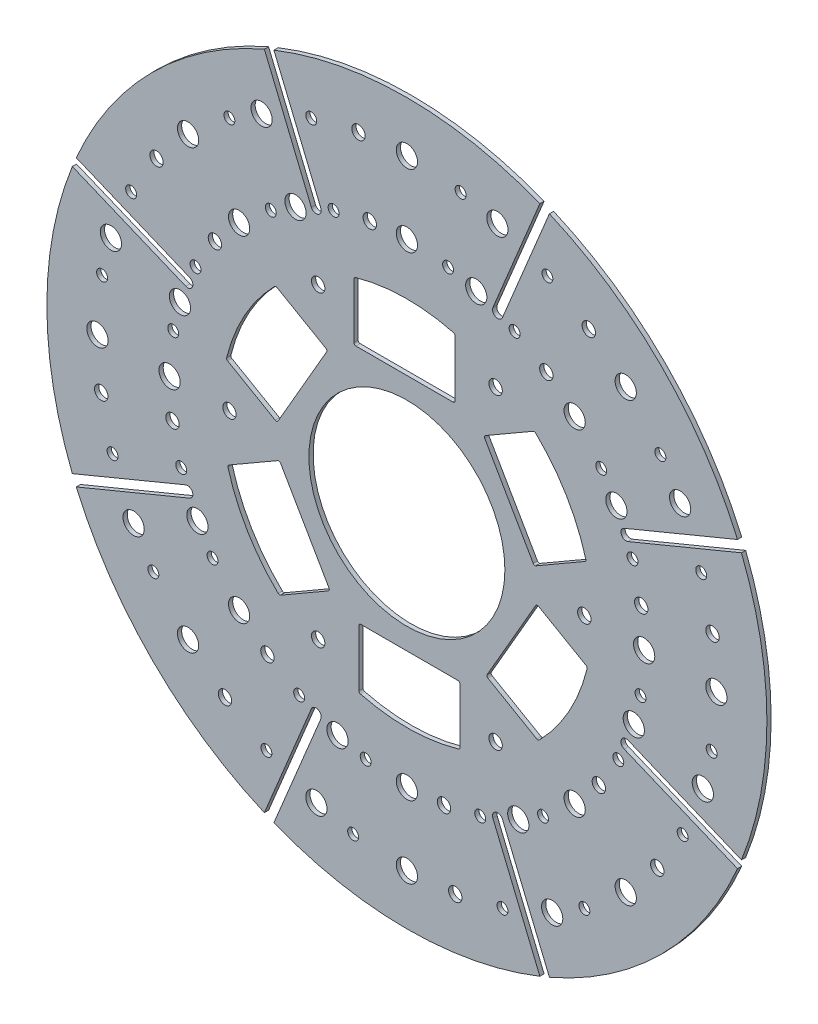
SolidWorks part; units mm, degrees
ref_plane "Plano frontal" through (0, 0, 0) normal (0, 0, 1) x (1, 0, 0)
ref_plane "Plano superior" through (0, 0, 0) normal (0, 1, 0) x (1, 0, 0)
ref_plane "Plano direito" through (0, 0, 0) normal (1, 0, 0) x (0, 0, -1)
sketch "Esboço1" plane through (0, 0, 0) normal (0, 0, 1) x (1, 0, 0)
  circle A0 centre (0, 0) radius 174.5
  circle A1 centre (0, 0) radius 47.5
  dimension "D1" = 95
  dimension "D2" = 349
extrude "Ressalto-extrusão1" add sketch "Esboço1" along normal blind 2.05
sketch "Esboço4" plane through (0, 0, 2.05) normal (0, 0, 1) x (1, 0, 0)
  line L0 (41.6989, 107.2029) -> (65.6818, 165.1028)
  line L1 (0, 115) -> (0, 0) construction
  line L5 (65.6818, 165.1028) -> (70.3012, 163.1894)
  line L6 (70.3012, 163.1894) -> (46.3183, 105.2894)
  line L10 (105.2894, 46.3183) -> (163.1894, 70.3012)
  line L11 (163.1894, 70.3012) -> (165.1028, 65.6818)
  line L12 (165.1028, 65.6818) -> (107.2029, 41.6989)
  line L16 (107.2029, -41.6989) -> (165.1028, -65.6818)
  line L17 (165.1028, -65.6818) -> (163.1894, -70.3012)
  line L18 (163.1894, -70.3012) -> (105.2894, -46.3183)
  line L22 (46.3183, -105.2894) -> (70.3012, -163.1894)
  line L23 (70.3012, -163.1894) -> (65.6818, -165.1028)
  line L24 (65.6818, -165.1028) -> (41.6989, -107.2029)
  line L28 (-41.6989, -107.2029) -> (-65.6818, -165.1028)
  line L29 (-65.6818, -165.1028) -> (-70.3012, -163.1894)
  line L30 (-70.3012, -163.1894) -> (-46.3183, -105.2894)
  line L34 (-105.2894, -46.3183) -> (-163.1894, -70.3012)
  line L35 (-163.1894, -70.3012) -> (-165.1028, -65.6818)
  line L36 (-165.1028, -65.6818) -> (-107.2029, -41.6989)
  line L40 (-107.2029, 41.6989) -> (-165.1028, 65.6818)
  line L41 (-165.1028, 65.6818) -> (-163.1894, 70.3012)
  line L42 (-163.1894, 70.3012) -> (-105.2894, 46.3183)
  line L46 (-46.3183, 105.2894) -> (-70.3012, 163.1894)
  line L47 (-70.3012, 163.1894) -> (-65.6818, 165.1028)
  line L48 (-65.6818, 165.1028) -> (-41.6989, 107.2029)
  arc A0 (41.6989, 107.2029) -> (46.3183, 105.2894) centre (44.0086, 106.2461) ccw
  arc A3 (105.2894, 46.3183) -> (107.2029, 41.6989) centre (106.2461, 44.0086) ccw
  arc A5 (107.2029, -41.6989) -> (105.2894, -46.3183) centre (106.2461, -44.0086) ccw
  arc A7 (46.3183, -105.2894) -> (41.6989, -107.2029) centre (44.0086, -106.2461) ccw
  arc A9 (-41.6989, -107.2029) -> (-46.3183, -105.2894) centre (-44.0086, -106.2461) ccw
  arc A11 (-105.2894, -46.3183) -> (-107.2029, -41.6989) centre (-106.2461, -44.0086) ccw
  arc A13 (-107.2029, 41.6989) -> (-105.2894, 46.3183) centre (-106.2461, 44.0086) ccw
  arc A15 (-46.3183, 105.2894) -> (-41.6989, 107.2029) centre (-44.0086, 106.2461) ccw
  point P85 (0, 0)
extrude "Corte-extrusão2" cut sketch "Esboço4" against normal blind 2.05
sketch "Esboço5" plane through (0, 0, 2.05) normal (0, 0, 1) x (1, 0, 0)
  line L0 (0, 0) -> (0, 150) construction
  line L1 (0, 0) -> (-23.4652, 148.1533) construction
  line L2 (0, 0) -> (-46.3525, 142.6585) construction
  line L3 (0, 0) -> (26.0472, 147.7212) construction
  line L4 (0, 0) -> (43.8558, 143.4457) construction
  circle A0 centre (0, 0) radius 115 construction
  circle A1 centre (0, 0) radius 150 construction
  circle A2 centre (-46.3525, 142.6585) radius 2.65
  circle A3 centre (-23.4652, 148.1533) radius 3.25
  circle A4 centre (0, 150) radius 5.15
  circle A5 centre (26.0472, 147.7212) radius 2.65
  circle A6 centre (43.8558, 143.4457) radius 5.15
  circle A7 centre (-35.537, 109.3715) radius 2.65
  circle A8 centre (-17.99, 113.5842) radius 3.25
  circle A9 centre (0, 115) radius 5.15
  circle A10 centre (19.9695, 113.2529) radius 2.65
  circle A11 centre (33.6227, 109.975) radius 5.15
  circle A12 centre (68.0986, 133.651) radius 2.65
  circle A13 centre (88.1678, 121.3525) radius 3.25
  circle A14 centre (106.066, 106.066) radius 5.15
  circle A15 centre (122.8728, 86.0365) radius 2.65
  circle A16 centre (132.4421, 70.4207) radius 5.15
  circle A17 centre (52.2089, 102.4658) radius 2.65
  circle A18 centre (67.5953, 93.037) radius 3.25
  circle A19 centre (81.3173, 81.3173) radius 5.15
  circle A20 centre (94.2025, 65.9613) radius 2.65
  circle A21 centre (101.539, 53.9892) radius 5.15
  circle A22 centre (142.6585, 46.3525) radius 2.65
  circle A23 centre (148.1533, 23.4652) radius 3.25
  circle A24 centre (150, 0) radius 5.15
  circle A25 centre (147.7212, -26.0472) radius 2.65
  circle A26 centre (143.4457, -43.8558) radius 5.15
  circle A27 centre (109.3715, 35.537) radius 2.65
  circle A28 centre (113.5842, 17.99) radius 3.25
  circle A29 centre (115, 0) radius 5.15
  circle A30 centre (113.2529, -19.9695) radius 2.65
  circle A31 centre (109.975, -33.6227) radius 5.15
  circle A32 centre (133.651, -68.0986) radius 2.65
  circle A33 centre (121.3525, -88.1678) radius 3.25
  circle A34 centre (106.066, -106.066) radius 5.15
  circle A35 centre (86.0365, -122.8728) radius 2.65
  circle A36 centre (70.4207, -132.4421) radius 5.15
  circle A37 centre (102.4658, -52.2089) radius 2.65
  circle A38 centre (93.037, -67.5953) radius 3.25
  circle A39 centre (81.3173, -81.3173) radius 5.15
  circle A40 centre (65.9613, -94.2025) radius 2.65
  circle A41 centre (53.9892, -101.539) radius 5.15
  circle A42 centre (46.3525, -142.6585) radius 2.65
  circle A43 centre (23.4652, -148.1533) radius 3.25
  circle A44 centre (0, -150) radius 5.15
  circle A45 centre (-26.0472, -147.7212) radius 2.65
  circle A46 centre (-43.8558, -143.4457) radius 5.15
  circle A47 centre (35.537, -109.3715) radius 2.65
  circle A48 centre (17.99, -113.5842) radius 3.25
  circle A49 centre (0, -115) radius 5.15
  circle A50 centre (-19.9695, -113.2529) radius 2.65
  circle A51 centre (-33.6227, -109.975) radius 5.15
  circle A52 centre (-68.0986, -133.651) radius 2.65
  circle A53 centre (-88.1678, -121.3525) radius 3.25
  circle A54 centre (-106.066, -106.066) radius 5.15
  circle A55 centre (-122.8728, -86.0365) radius 2.65
  circle A56 centre (-132.4421, -70.4207) radius 5.15
  circle A57 centre (-52.2089, -102.4658) radius 2.65
  circle A58 centre (-67.5953, -93.037) radius 3.25
  circle A59 centre (-81.3173, -81.3173) radius 5.15
  circle A60 centre (-94.2025, -65.9613) radius 2.65
  circle A61 centre (-101.539, -53.9892) radius 5.15
  circle A62 centre (-142.6585, -46.3525) radius 2.65
  circle A63 centre (-148.1533, -23.4652) radius 3.25
  circle A64 centre (-150, 0) radius 5.15
  circle A65 centre (-147.7212, 26.0472) radius 2.65
  circle A66 centre (-143.4457, 43.8558) radius 5.15
  circle A67 centre (-109.3715, -35.537) radius 2.65
  circle A68 centre (-113.5842, -17.99) radius 3.25
  circle A69 centre (-115, 0) radius 5.15
  circle A70 centre (-113.2529, 19.9695) radius 2.65
  circle A71 centre (-109.975, 33.6227) radius 5.15
  circle A72 centre (-133.651, 68.0986) radius 2.65
  circle A73 centre (-121.3525, 88.1678) radius 3.25
  circle A74 centre (-106.066, 106.066) radius 5.15
  circle A75 centre (-86.0365, 122.8728) radius 2.65
  circle A76 centre (-70.4207, 132.4421) radius 5.15
  circle A77 centre (-102.4658, 52.2089) radius 2.65
  circle A78 centre (-93.037, 67.5953) radius 3.25
  circle A79 centre (-81.3173, 81.3173) radius 5.15
  circle A80 centre (-65.9613, 94.2025) radius 2.65
  circle A81 centre (-53.9892, 101.539) radius 5.15
  point P166 (0, 0)
  dimension "D1" = 9
  dimension "D2" = 9
  dimension "D5" = 5.3
  dimension "D6" = 6.5
  dimension "D7" = 10.3
  dimension "D8" = 5.3
  dimension "D9" = 10.3
  dimension "D10" = 230
  dimension "D3" = 10
  dimension "D4" = 7
  dimension "D11" = 8
extrude "Corte-extrusão3" cut sketch "Esboço5" against normal blind 2.05
sketch "Esboço6" plane through (0, 0, 2.05) normal (0, 0, 1) x (1, 0, 0)
  line L1 (-25.6881, 57.8268) -> (23.3119, 57.8268)
  line L2 (-25.6881, 57.8268) -> (-25.6881, 86.2562)
  line L3 (23.3119, 57.8268) -> (23.3119, 86.9284)
  line L5 (37.2355, 51.1599) -> (61.7355, 8.7247)
  line L6 (37.2355, 51.1599) -> (61.856, 65.3746)
  line L7 (61.7355, 8.7247) -> (86.9382, 23.2755)
  line L9 (62.9236, -6.6669) -> (38.4236, -49.1022)
  line L10 (62.9236, -6.6669) -> (87.544, -20.8816)
  line L11 (38.4236, -49.1022) -> (63.6263, -63.653)
  line L13 (25.6881, -57.8268) -> (-23.3119, -57.8268)
  line L14 (25.6881, -57.8268) -> (25.6881, -86.2562)
  line L15 (-23.3119, -57.8268) -> (-23.3119, -86.9284)
  line L17 (-37.2355, -51.1599) -> (-61.7355, -8.7247)
  line L18 (-37.2355, -51.1599) -> (-61.856, -65.3746)
  line L19 (-61.7355, -8.7247) -> (-86.9382, -23.2755)
  line L21 (-62.9236, 6.6669) -> (-38.4236, 49.1022)
  line L22 (-62.9236, 6.6669) -> (-87.544, 20.8816)
  line L23 (-38.4236, 49.1022) -> (-63.6263, 63.653)
  arc A0 (61.856, 65.3746) -> (86.9382, 23.2755) centre (0, 0) cw
  arc A1 (-25.6881, 86.2562) -> (23.3119, 86.9284) centre (0, 0) cw
  arc A4 (87.544, -20.8816) -> (63.6263, -63.653) centre (0, 0) cw
  arc A6 (25.6881, -86.2562) -> (-23.3119, -86.9284) centre (0, 0) cw
  arc A8 (-61.856, -65.3746) -> (-86.9382, -23.2755) centre (0, 0) cw
  arc A10 (-87.544, 20.8816) -> (-63.6263, 63.653) centre (0, 0) cw
  point P41 (0, 0)
  dimension "D1" = 6
  dimension "D3" = 49
extrude "Corte-extrusão5" cut sketch "Esboço6" against normal blind 2.05
sketch "Esboço8" plane through (0, 0, 2.05) normal (0, 0, 1) x (1, 0, 0)
  circle A0 centre (0, 0) radius 86 construction
  circle A2 centre (43, 74.4782) radius 3.25
  circle A4 centre (86, 0) radius 3.25
  circle A6 centre (43, -74.4782) radius 3.25
  circle A8 centre (-43, -74.4782) radius 3.25
  circle A10 centre (-86, 0) radius 3.25
  circle A12 centre (-43, 74.4782) radius 3.25
  point P29 (0, 0)
extrude "Corte-extrusão6" cut sketch "Esboço8" against normal blind 2.05
fillet "Filete1" radius 1 24 edges at (-87.544, 20.8816, 1.025) (-62.9236, 6.6669, 1.025) (-38.4236, 49.1022, 1.025) (-63.6263, 63.653, 1.025) (-61.856, -65.3746, 1.025) (-37.2355, -51.1599, 1.025) (-86.9382, -23.2755, 1.025) (-61.7355, -8.7247, 1.025) (-23.3119, -57.8268, 1.025) (-23.3119, -86.9284, 1.025) (25.6881, -86.2562, 1.025) (25.6881, -57.8268, 1.025) (87.544, -20.8816, 1.025) (62.9236, -6.6669, 1.025) (38.4236, -49.1022, 1.025) (63.6263, -63.653, 1.025) (61.7355, 8.7247, 1.025) (86.9382, 23.2755, 1.025) (37.2355, 51.1599, 1.025) (61.856, 65.3746, 1.025) (-25.6881, 86.2562, 1.025) (-25.6881, 57.8268, 1.025) (23.3119, 57.8268, 1.025) (23.3119, 86.9284, 1.025)
